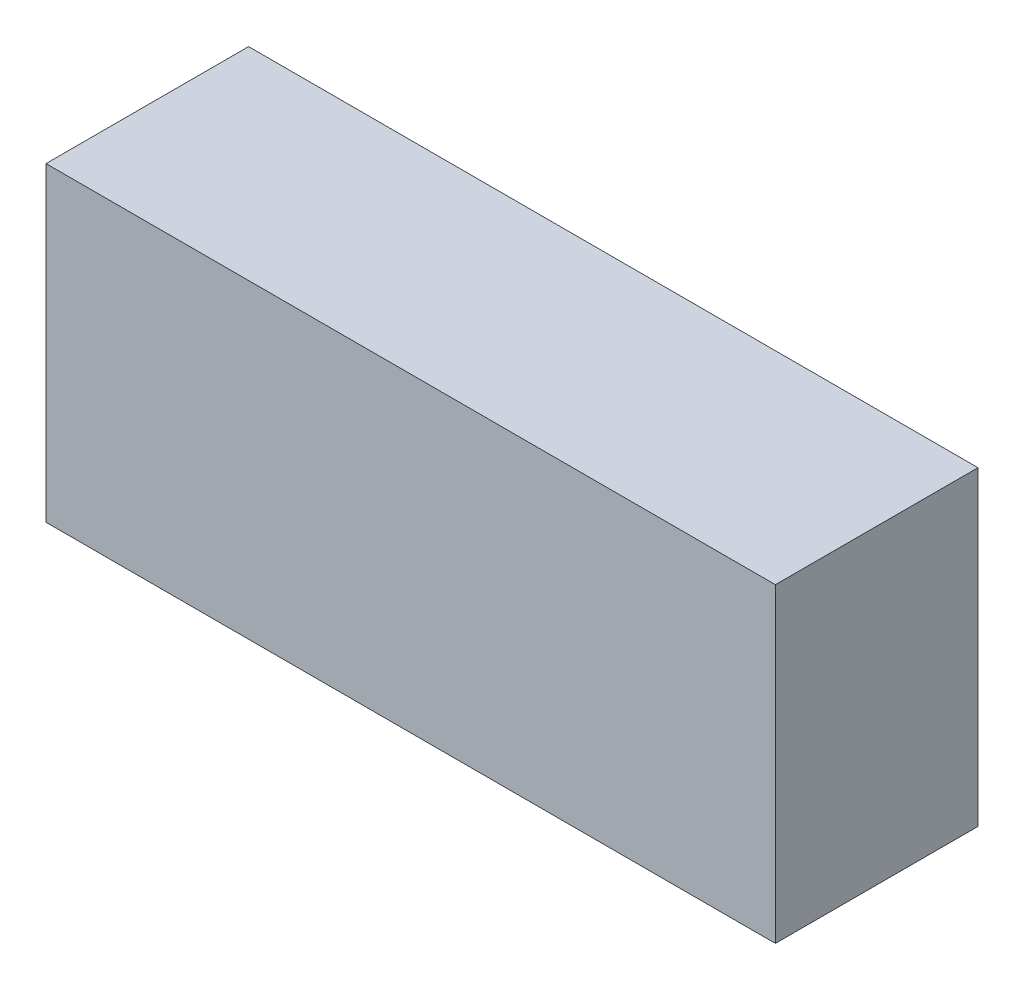
SolidWorks part; units mm, degrees
ref_plane "前视基准面" through (0, 0, 0) normal (0, 0, 1) x (1, 0, 0)
ref_plane "上视基准面" through (0, 0, 0) normal (0, 1, 0) x (1, 0, 0)
ref_plane "右视基准面" through (0, 0, 0) normal (1, 0, 0) x (0, 0, -1)
sketch "草图1" plane through (0, 0, 0) normal (0, 0, 1) x (1, 0, 0)
  line L0 (0, 0) -> (54, 0)
  line L1 (54, 0) -> (54, 23)
  line L2 (54, 23) -> (0, 23)
  line L3 (0, 23) -> (0, 0)
  dimension "D1" = 54
  dimension "D2" = 23
extrude "凸台-拉伸1" add sketch "草图1" along normal blind 15
sketch "草图2" plane through (0, 0, 0) normal (0, 0, -1) x (-1, 0, 0)
  text T0 "<b>STM32F103</b>" font "汉仪长仿宋体" height 3.5
